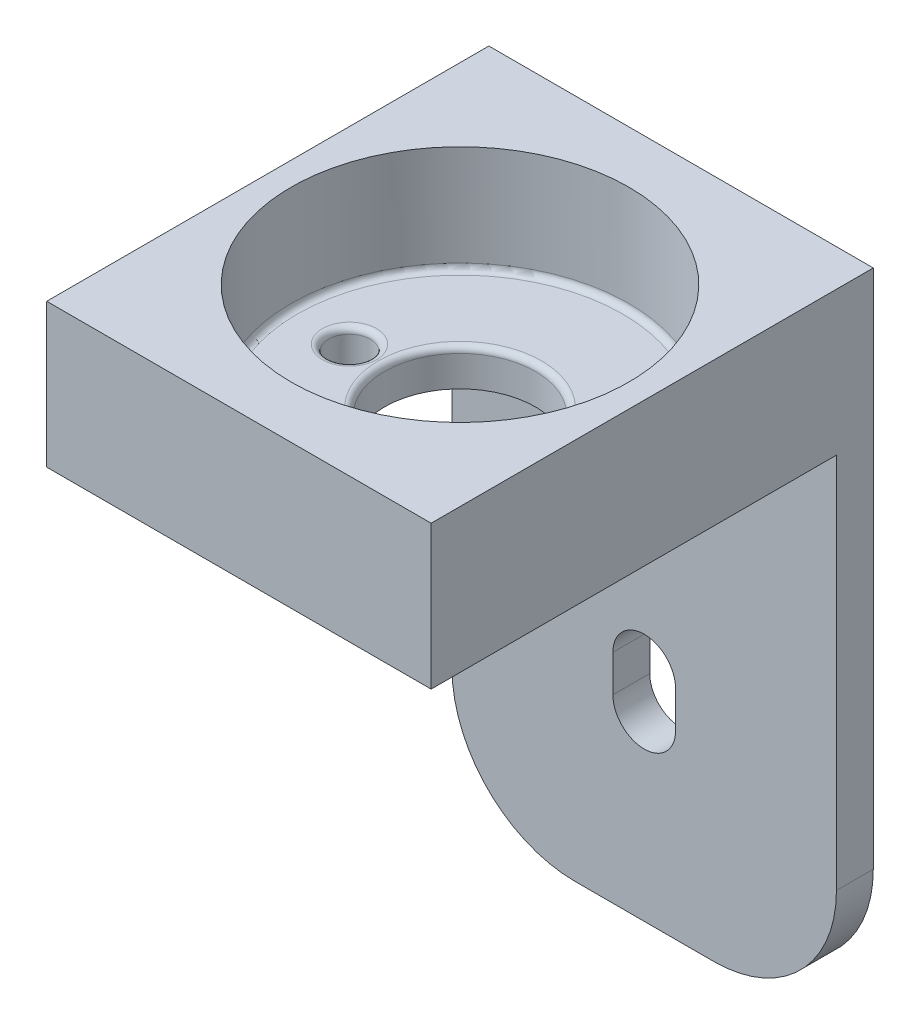
SolidWorks part; units mm, degrees
ref_plane "Front Plane" through (0, 0, 0) normal (0, 0, 1) x (1, 0, 0)
ref_plane "Top Plane" through (0, 0, 0) normal (0, 1, 0) x (1, 0, 0)
ref_plane "Right Plane" through (0, 0, 0) normal (1, 0, 0) x (0, 0, -1)
sketch "Sketch1" plane through (0, 0, 0) normal (0, 0, 1) x (1, 0, 0)
  line L1 (15.65, 26.2) -> (-15.65, 26.2)
  line L2 (15.65, 26.2) -> (15.65, -26.2)
  line L3 (15.65, -26.2) -> (-15.65, -26.2)
  line L4 (-15.65, 26.2) -> (-15.65, -26.2)
  line L5 (15.65, 26.2) -> (-15.65, -26.2) construction
  line L6 (15.65, -26.2) -> (-15.65, 26.2) construction
  point P0 (0, 0)
  dimension "D1" = 52.4
  dimension "D2" = 31.3
extrude "Boss-Extrude1" add sketch "Sketch1" along normal blind 3
sketch "Sketch2" plane through (0, 0, 3) normal (0, 0, 1) x (1, 0, 0)
  line L0 (15.65, -26.2) -> (15.65, 26.2) construction
  line L1 (15.65, 17.5) -> (-15.65, 17.5)
  line L2 (15.65, 17.5) -> (15.65, 14.5)
  line L3 (15.65, 14.5) -> (-15.65, 14.5)
  line L4 (-15.65, 17.5) -> (-15.65, 14.5)
  line L5 (-15.65, 26.2) -> (-15.65, -26.2) construction
  line L6 (-12.6, 17.5) -> (12.6, 17.5) construction
  dimension "D1" = 3
extrude "Boss-Extrude2" add sketch "Sketch2" along normal blind 33
sketch "Sketch3" plane through (0, 0, 3) normal (0, 0, 1) x (1, 0, 0)
  line L1 (15.65, 26.2) -> (-15.65, 26.2)
  line L2 (15.65, 26.2) -> (15.65, 17.5)
  line L3 (15.65, 17.5) -> (-15.65, 17.5)
  line L4 (-15.65, 26.2) -> (-15.65, 17.5)
extrude "Boss-Extrude3" add sketch "Sketch3" along normal up to surface (33 mm away) up to face at (0, 16, 36)
sketch "Sketch5" plane through (0, 26.2, 0) normal (0, 1, 0) x (1, 0, 0)
  circle A0 centre (0, -18) radius 13.75
  dimension "D1" = 27.5
extrude "Cut-Extrude1" cut sketch "Sketch5" against normal offset from surface (8.7 mm away) 3 up to face at (0, 14.5, 19.5)
sketch "Sketch6" plane through (0, 17.5, 0) normal (0, 1, 0) x (1, 0, 0)
  circle A0 centre (0, -18) radius 6.15
  dimension "D1" = 12.3
extrude "Cut-Extrude2" cut sketch "Sketch6" against normal up to surface (3 mm away) up to face at (0, 14.5, 19.5)
sketch "Sketch7" plane through (0, 14.5, 0) normal (0, -1, 0) x (1, 0, 0)
  line L0 (-15.65, 18) -> (6.15, 18) construction
  line L1 (0, 24.15) -> (0, 11.85) construction
  line L3 (-15.65, 36) -> (-15.65, 3) construction
  circle A0 centre (-9, 18) radius 1.7
  circle A1 centre (0, 18) radius 6.15 construction
  circle A2 centre (9, 18) radius 1.7
  dimension "D1" = 9
  dimension "D2" = 3.4
extrude "Cut-Extrude3" cut sketch "Sketch7" along normal up to surface and the other way up to surface up to face at (0, -26.2, 1.5) other way up to face at (-6.15, 17.5, 18)
fillet "Fillet4" radius 0.5 4 edges at (-6.15, 17.5, 18) (7.3, 17.5, 18) (-10.7, 17.5, 18) (-13.75, 17.5, 18)
sketch "Sketch10" plane through (0, 0, 0) normal (0, 0, -1) x (-1, 0, 0)
  line L0 (0, -11.5) -> (0, -8.5) construction
  line L1 (-2.55, -11.5) -> (-2.55, -8.5)
  line L2 (2.55, -11.5) -> (2.55, -8.5)
  line L3 (0, 8.5) -> (0, 11.5) construction
  line L4 (-2.55, 8.5) -> (-2.55, 11.5)
  line L5 (2.55, 8.5) -> (2.55, 11.5)
  arc A3 (-2.55, -11.5) -> (2.55, -11.5) centre (0, -11.5) ccw
  arc A4 (2.55, -8.5) -> (-2.55, -8.5) centre (0, -8.5) ccw
  arc A5 (-2.55, 8.5) -> (2.55, 8.5) centre (0, 8.5) ccw
  arc A6 (2.55, 11.5) -> (-2.55, 11.5) centre (0, 11.5) ccw
  arc A7 (0, -7.45) -> (0, -12.55) centre (0, -10) ccw construction
  arc A8 (0, -12.55) -> (0, -7.45) centre (0, -10) ccw construction
  circle A9 centre (0, 10) radius 2.55 construction
  point P3 (0, -10)
  point P11 (0, 10)
  dimension "D1" = 3
extrude "Cut-Extrude6" cut sketch "Sketch10" against normal up to surface (3 mm away) up to face at (0, -5.85, 3)
fillet "Fillet5" radius 10 2 edges at (15.65, -26.2, 1.5) (-15.65, -26.2, 1.5)
